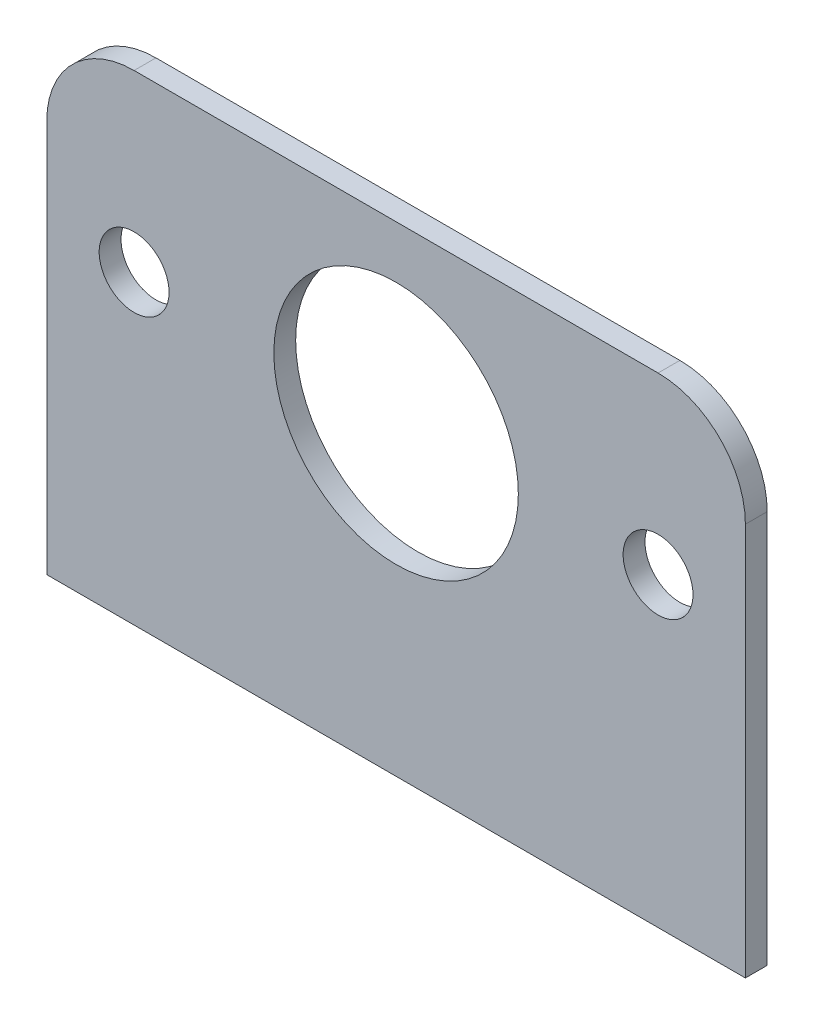
SolidWorks part; units mm, degrees
material "AISI 4130 Steel, annealed at 865C"
ref_plane "Front Plane" through (0, 0, 0) normal (0, 0, 1) x (1, 0, 0)
ref_plane "Top Plane" through (0, 0, 0) normal (0, 1, 0) x (1, 0, 0)
ref_plane "Right Plane" through (0, 0, 0) normal (1, 0, 0) x (0, 0, -1)
sketch "Sketch1" plane through (0, 0, 0) normal (0, 0, 1) x (1, 0, 0)
  line L0 (-25.4, 0) -> (25.4, 0) construction
  line L1 (-25.4, 12.7) -> (25.4, 12.7)
  line L2 (-25.4, 12.7) -> (-25.4, -12.7)
  line L3 (-25.4, -12.7) -> (25.4, -12.7)
  line L4 (25.4, 12.7) -> (25.4, -12.7)
  line L5 (-25.4, 12.7) -> (25.4, -12.7) construction
  line L6 (-25.4, -12.7) -> (25.4, 12.7) construction
  line L7 (-19.05, 0) -> (19.05, 0) construction
  circle A0 centre (0, 0) radius 8.89
  circle A1 centre (19.05, 0) radius 2.54
  circle A2 centre (-19.05, 0) radius 2.54
  point P0 (0, 0)
  point P9 (25.4, 0)
  point P14 (0, 0)
  dimension "D1" = 17.78
  dimension "D4" = 5.08
  dimension "D2" = 50.8
  dimension "D3" = 25.4
  dimension "D5" = 38.1
extrude "Boss-Extrude1" add sketch "Sketch1" along normal blind 1.5875
sketch "Sketch3" plane through (0, 0, 0) normal (0, 0, 1) x (1, 0, 0)
  line L0 (25.4, -12.7) -> (25.4, 12.7) construction
  line L1 (-25.4, -12.7) -> (25.4, -12.7)
  line L2 (-25.4, -12.7) -> (-25.4, -22.225)
  line L3 (-25.4, -22.225) -> (25.4, -22.225)
  line L4 (25.4, -12.7) -> (25.4, -22.225)
  line L5 (0, -22.225) -> (0, -12.7) construction
  line L6 (-25.4, -17.4625) -> (25.4, -17.4625) construction
  point P264 (0, -17.4625)
  dimension "D1" = 9.525
extrude "Boss-Extrude2" add sketch "Sketch3" along normal up to surface (1.5875 mm away) up to face at (21.59, 0, 1.5875)
fillet "Fillet1" radius 6.35 2 edges at (-25.4, 12.7, 0.7937) (25.4, 12.7, 0.7937)
